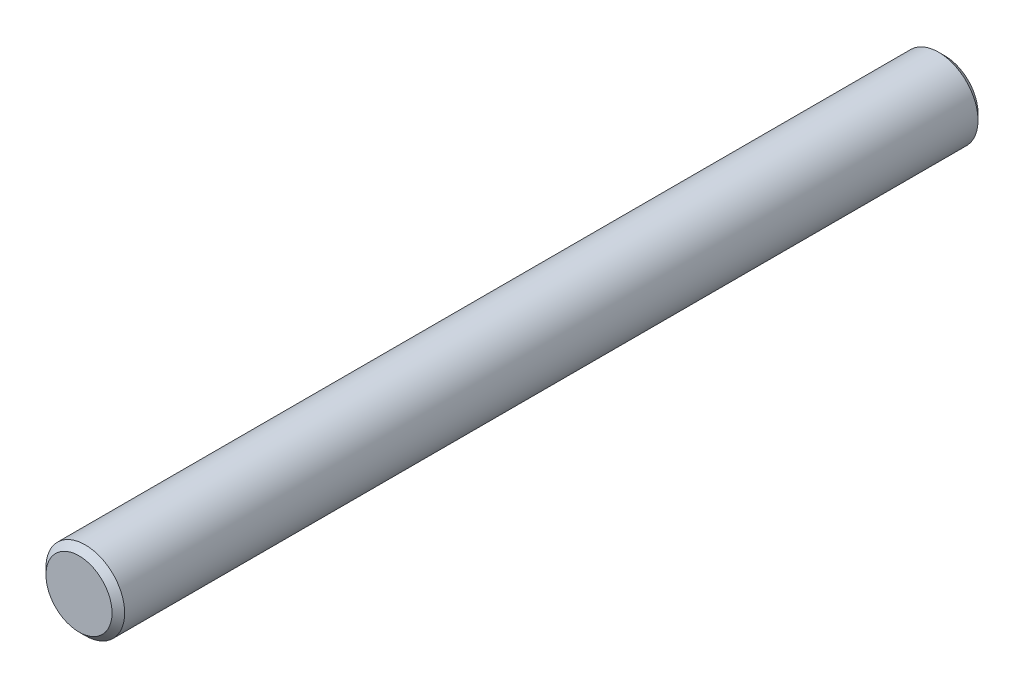
SolidWorks part; units mm, degrees
ref_plane "Front Plane" through (0, 0, 0) normal (0, 0, 1) x (1, 0, 0)
ref_plane "Top Plane" through (0, 0, 0) normal (0, 1, 0) x (1, 0, 0)
ref_plane "Right Plane" through (0, 0, 0) normal (1, 0, 0) x (0, 0, -1)
sketch "Sketch1" plane through (0, 0, 0) normal (0, 0, 1) x (1, 0, 0)
  circle A0 centre (0, 0) radius 3.175
  dimension "D1" = 6.35
extrude "Boss-Extrude2" add sketch "Sketch1" along normal blind 69.85
chamfer "Chamfer2" distance 0.508 angle 45 2 edges at (3.175, 0, 0) (3.175, 0, 69.85)
